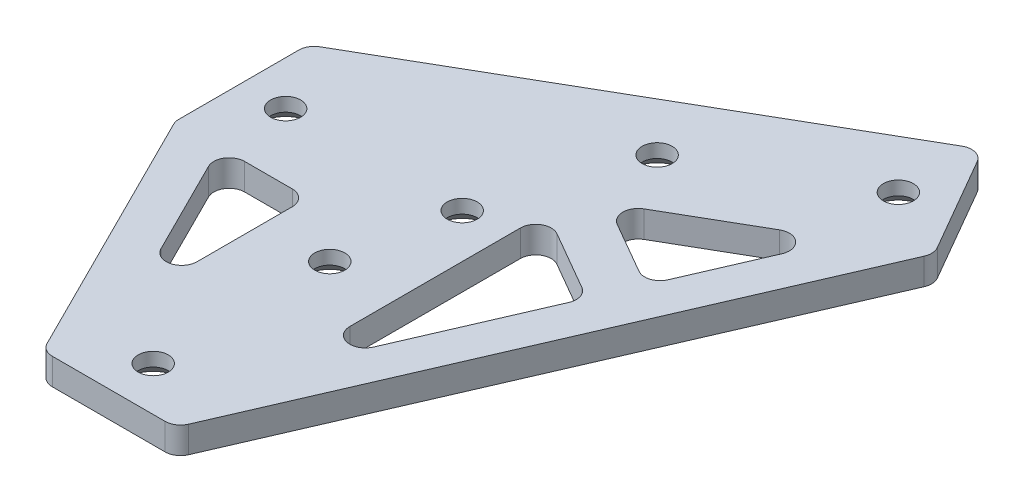
SolidWorks part; units mm, degrees
ref_plane "正面" through (0, 0, 0) normal (0, 0, 1) x (1, 0, 0)
ref_plane "平面" through (0, 0, 0) normal (0, 1, 0) x (1, 0, 0)
ref_plane "右側面" through (0, 0, 0) normal (1, 0, 0) x (0, 0, -1)
sketch "ｽｹｯﾁ2" plane through (0, 0.3953, 0) normal (0, 1, 0) x (1, 0, 0)
  line L0 (275.032, 154.7676) -> (267.532, 167.7579) construction
  line L1 (267.532, 167.7579) -> (163.6089, 107.7579) construction
  line L2 (163.6089, 107.7579) -> (171.1089, 94.7676) construction
  line L3 (171.1089, 94.7676) -> (275.032, 154.7676) construction
  line L4 (171.1089, 79.7676) -> (156.1089, 79.7676) construction
  line L5 (156.1089, 79.7676) -> (156.1089, -61.2324) construction
  line L6 (156.1089, -61.2324) -> (171.1089, -61.2324) construction
  line L7 (171.1089, -61.2324) -> (171.1089, 79.7676) construction
  line L8 (171.1089, 79.7676) -> (171.1089, 94.7676) construction
  line L9 (171.1089, 94.7676) -> (-48.8911, 94.7676) construction
  line L10 (-48.8911, 94.7676) -> (-48.8911, 79.7676) construction
  line L11 (-48.8911, 79.7676) -> (171.1089, 79.7676) construction
  line L12 (275.032, 154.7676) -> (267.532, 167.7579) construction
  line L13 (267.532, 167.7579) -> (163.6089, 107.7579) construction
  line L14 (163.6089, 107.7579) -> (171.1089, 94.7676) construction
  line L15 (171.1089, 94.7676) -> (275.032, 154.7676) construction
  line L16 (171.1089, 79.7676) -> (156.1089, 79.7676) construction
  line L17 (156.1089, 79.7676) -> (156.1089, -61.2324) construction
  line L18 (156.1089, -61.2324) -> (171.1089, -61.2324) construction
  line L19 (171.1089, -61.2324) -> (171.1089, 79.7676) construction
  line L20 (171.1089, 79.7676) -> (171.1089, 94.7676) construction
  line L21 (171.1089, 94.7676) -> (-48.8911, 94.7676) construction
  line L22 (-48.8911, 94.7676) -> (-48.8911, 79.7676) construction
  line L23 (-48.8911, 79.7676) -> (171.1089, 79.7676) construction
  line L24 (0, 15) -> (103.923, 75) construction
  line L25 (0, 0) -> (-220, 0) construction
  line L26 (0, 0) -> (0, 15) construction
  line L27 (0, 15) -> (-220, 15) construction
  line L28 (-220, 0) -> (-220, 15) construction
  line L29 (0, 0) -> (-15, 0) construction
  line L30 (0, 0) -> (0, -141) construction
  line L31 (0, -141) -> (-15, -141) construction
  line L32 (-15, 0) -> (-15, -141) construction
  line L33 (103.923, 75) -> (96.423, 87.9904) construction
  line L34 (96.423, 87.9904) -> (-7.5, 27.9904) construction
  line L35 (-7.5, 27.9904) -> (0, 15) construction
  dimension "D1" = 15
  dimension "D2" = 220
  dimension "D3" = 141
  dimension "D4" = 15
  dimension "D5" = 120
  dimension "D6" = 15
  dimension "D7" = 120
sketch "ｽｹｯﾁ4" plane through (0, 0, 0) normal (0, 1, 0) x (1, 0, 0)
  line L0 (103.923, 75) -> (96.423, 87.9904) construction
  line L1 (0, 15) -> (103.923, 75) construction
  line L2 (96.423, 87.9904) -> (-7.5, 27.9904) construction
  line L3 (-7.5, 27.9904) -> (0, 15) construction
  line L4 (0, -141) -> (-15, -141) construction
  line L5 (0, 0) -> (0, -141) construction
  line L6 (-15, 0) -> (-15, -141) construction
  line L7 (0, 0) -> (0, 15) construction
  line L8 (-220, 0) -> (-220, 15) construction
  line L9 (0, 0) -> (-220, 0) construction
  line L10 (0, 15) -> (-220, 15) construction
  line L11 (103.923, 75) -> (96.423, 87.9904) construction
  line L12 (0, 15) -> (103.923, 75) construction
  line L13 (96.423, 87.9904) -> (-7.5, 27.9904) construction
  line L14 (-7.5, 27.9904) -> (0, 15) construction
  line L15 (0, -141) -> (-15, -141) construction
  line L16 (0, 0) -> (0, -141) construction
  line L17 (-15, 0) -> (-15, -141) construction
  line L18 (0, 0) -> (0, 15) construction
  line L19 (-220, 0) -> (-220, 15) construction
  line L20 (0, 0) -> (-220, 0) construction
  line L21 (0, 15) -> (-220, 15) construction
  line L22 (-3.75, 21.4952) -> (17.9006, 33.9952) construction
  line L23 (0, 7.5) -> (-25, 7.5) construction
  line L24 (-7.5, 0) -> (-7.5, -25) construction
  line L25 (-30, 0) -> (-30, 15)
  line L26 (-30, 15) -> (18.4808, 42.9904)
  line L27 (18.4808, 42.9904) -> (25.9808, 30)
  line L28 (25.9808, 30) -> (0, -30)
  line L29 (0, -30) -> (-15, -30)
  line L30 (-15, -30) -> (-30, 0)
  circle A0 centre (0.5801, 23.9952) radius 1.6
  circle A1 centre (-5, 7.5) radius 1.6
  circle A2 centre (-7.5, -5) radius 1.6
  circle A3 centre (-7.5, -25) radius 1.6
  circle A4 centre (-25, 7.5) radius 1.6
  circle A5 centre (17.9006, 33.9952) radius 1.6
  dimension "D4" = 3.2
  dimension "D5" = 3.2
  dimension "D6" = 3.2
  dimension "D7" = 3.2
  dimension "D8" = 3.2
  dimension "D9" = 3.2
  dimension "D1" = 25
  dimension "D2" = 25
  dimension "D3" = 25
  dimension "D10" = 20
  dimension "D11" = 20
  dimension "D12" = 20
  dimension "D13" = 5
  dimension "D14" = 5
  dimension "D15" = 5
extrude "ﾎﾞｽ - 押し出し1" add sketch "ｽｹｯﾁ4" along normal mid plane 3
sketch "ｽｹｯﾁ5" plane through (0, 1.5, 0) normal (0, 1, 0) x (1, 0, 0)
  line L0 (-7.5, 27.9904) -> (0, 15) construction
  line L1 (0, 15) -> (103.923, 75) construction
  line L2 (0, 0) -> (0, 15) construction
  line L3 (0, 15) -> (-220, 15) construction
  line L4 (0, 0) -> (-220, 0) construction
  line L5 (-15, 0) -> (-15, -141) construction
  line L6 (-30, 0) -> (-15, -30)
  line L7 (-15, -30) -> (0, -30)
  line L8 (0, -30) -> (25.9808, 30)
  line L9 (25.9808, 30) -> (18.4808, 42.9904)
  line L10 (18.4808, 42.9904) -> (-30, 15)
  line L11 (-30, 15) -> (-30, 0)
  line L12 (-30, 0) -> (-15, -30)
  line L13 (-15, -30) -> (0, -30)
  line L14 (0, -30) -> (25.9808, 30)
  line L15 (25.9808, 30) -> (18.4808, 42.9904)
  line L16 (18.4808, 42.9904) -> (-30, 15)
  line L17 (-30, 15) -> (-30, 0)
  line L18 (0, 0) -> (0, -141) construction
  line L19 (-7.5, 27.9904) -> (0, 15)
  line L20 (0, 15) -> (103.923, 75)
  line L21 (0, 0) -> (0, 15)
  line L22 (0, 15) -> (-220, 15)
  line L23 (0, 0) -> (-220, 0)
  line L24 (-15, 0) -> (-15, -141)
  line L25 (0, 0) -> (0, -141)
  line L26 (-2.9552, -25.5) -> (20.9517, 29.7106)
  line L27 (20.9517, 29.7106) -> (16.8336, 36.8433)
  line L28 (16.8336, 36.8433) -> (-25.5, 12.4019)
  line L29 (-25.5, 12.4019) -> (-25.5, 1.0623)
  line L30 (-25.5, 1.0623) -> (-12.2188, -25.5)
  line L31 (-12.2188, -25.5) -> (-2.9552, -25.5)
  line L32 (0, 15) -> (11.6654, 8.265) construction
  line L33 (0, 15) -> (-10.5, 21.0622) construction
  line L34 (-13, 19.6188) -> (10.6654, 5.9555)
  line L37 (-21, 15) -> (-5.25, 24.0933) construction
  line L38 (12.6654, 10.5744) -> (-8, 22.5056)
  line L40 (0, 15) -> (3.4641, 13)
  line L41 (0, 15) -> (-3.4641, 17)
  line L42 (-4.6188, 15) -> (-2.3094, 19)
  line L43 (0, 7) -> (6.9282, 19)
  line L44 (1.25, 17.1651) -> (-9.25, 23.2272) construction
  line L47 (-1.25, 12.8349) -> (10.4154, 6.0999) construction
  circle A1 centre (0.5801, 23.9952) radius 1.6
  circle A2 centre (0.5801, 23.9952) radius 1.6
  circle A3 centre (-5, 7.5) radius 1.6
  circle A4 centre (-5, 7.5) radius 1.6
  circle A5 centre (-7.5, -5) radius 1.6
  circle A6 centre (-7.5, -5) radius 1.6
  circle A7 centre (-7.5, -25) radius 1.6
  circle A8 centre (-7.5, -25) radius 1.6
  circle A9 centre (-25, 7.5) radius 1.6
  circle A10 centre (-25, 7.5) radius 1.6
  circle A11 centre (17.9006, 33.9952) radius 1.6
  circle A12 centre (17.9006, 33.9952) radius 1.6
  point P58 (-3.4641, 17)
  point P61 (3.4641, 13)
  dimension "D9" = 2.5
  dimension "D12" = 60
  dimension "D13" = 4
  dimension "D14" = 4
  dimension "D1" = 0
  dimension "D2" = 0
  dimension "D3" = 0
  dimension "D4" = 0
  dimension "D5" = 0
  dimension "D6" = 0
  dimension "D7" = 0
  dimension "D8" = 4.5
extrude "ｶｯﾄ - 押し出し2" cut sketch "ｽｹｯﾁ5" against normal blind 3 contours L43 L38 L26 L20 | L38 L43 L20 | L21 L43 L34 | L43 L21 L25 L26 L34 | L23 L30 L24
fillet "ﾌｨﾚｯﾄ2" radius 1.75 15 edges at (-15, 0, 19.9377) (0, 0, 18.6752) (10.6654, 0, -5.9555) (12.6654, 0, -10.5744) (2.5, 0, -16.4434) (19.4424, 0, -26.2251) (-24.9688, 0, 0) (-15, 0, 30) (0, 0, 30) (25.9808, 0, -30) (18.4808, 0, -42.9904) (-30, 0, -15) (-30, 0, 0) (0, 0, -12.1132) (-15, 0, 0)
sketch "ｽｹｯﾁ6" plane through (0, -1.5, 0) normal (0, -1, 0) x (1, 0, 0)
  line L3 (2.625, -10.5977) -> (9.3148, -6.7353)
  line L4 (0, 10.2297) -> (0, -9.0822)
  line L5 (10.0457, -4.5244) -> (3.3559, 10.9251)
  line L6 (2.625, -10.5977) -> (9.3148, -6.7353)
  line L7 (0, 10.2297) -> (0, -9.0822)
  line L8 (10.0457, -4.5244) -> (3.3559, 10.9251)
  line L9 (-15, 1.75) -> (-15, 12.5246)
  line L10 (-22.1373, 0) -> (-16.75, 0)
  line L11 (-18.3152, 13.3072) -> (-23.7025, 2.5326)
  line L12 (-15, 1.75) -> (-15, 12.5246)
  line L13 (-22.1373, 0) -> (-16.75, 0)
  line L14 (-18.3152, 13.3072) -> (-23.7025, 2.5326)
  line L15 (10.9648, -11.5562) -> (5.125, -14.9278)
  line L16 (17.339, -21.3674) -> (13.4457, -12.3764)
  line L17 (5.125, -17.9589) -> (14.8581, -23.5783)
  line L18 (10.9648, -11.5562) -> (5.125, -14.9278)
  line L19 (17.339, -21.3674) -> (13.4457, -12.3764)
  line L20 (5.125, -17.9589) -> (14.8581, -23.5783)
  circle A1 centre (-25, -7.5) radius 1.6
  circle A2 centre (-25, -7.5) radius 1.6
  arc A3 (0, -9.0822) -> (2.625, -10.5977) centre (1.75, -9.0822) ccw
  arc A4 (3.3559, 10.9251) -> (0, 10.2297) centre (1.75, 10.2297) ccw
  arc A5 (9.3148, -6.7353) -> (10.0457, -4.5244) centre (8.4398, -5.2198) ccw
  arc A6 (0, -9.0822) -> (2.625, -10.5977) centre (1.75, -9.0822) ccw
  arc A7 (3.3559, 10.9251) -> (0, 10.2297) centre (1.75, 10.2297) ccw
  arc A8 (9.3148, -6.7353) -> (10.0457, -4.5244) centre (8.4398, -5.2198) ccw
  arc A9 (-16.75, 0) -> (-15, 1.75) centre (-16.75, 1.75) ccw
  arc A10 (-23.7025, 2.5326) -> (-22.1373, 0) centre (-22.1373, 1.75) ccw
  arc A11 (-15, 12.5246) -> (-18.3152, 13.3072) centre (-16.75, 12.5246) ccw
  arc A12 (-16.75, 0) -> (-15, 1.75) centre (-16.75, 1.75) ccw
  arc A13 (-23.7025, 2.5326) -> (-22.1373, 0) centre (-22.1373, 1.75) ccw
  arc A14 (-15, 12.5246) -> (-18.3152, 13.3072) centre (-16.75, 12.5246) ccw
  circle A15 centre (-7.5, 5) radius 1.6
  circle A16 centre (-7.5, 5) radius 1.6
  circle A17 centre (0.5801, -23.9952) radius 1.6
  circle A18 centre (0.5801, -23.9952) radius 1.6
  circle A19 centre (-5, -7.5) radius 1.6
  circle A20 centre (-5, -7.5) radius 1.6
  circle A21 centre (-7.5, 25) radius 1.6
  circle A22 centre (-7.5, 25) radius 1.6
  circle A23 centre (17.9006, -33.9952) radius 1.6
  circle A24 centre (17.9006, -33.9952) radius 1.6
  arc A27 (13.4457, -12.3764) -> (10.9648, -11.5562) centre (11.8398, -13.0717) ccw
  arc A28 (14.8581, -23.5783) -> (17.339, -21.3674) centre (15.7331, -22.0628) ccw
  arc A29 (5.125, -14.9278) -> (5.125, -17.9589) centre (6, -16.4434) ccw
  arc A30 (13.4457, -12.3764) -> (10.9648, -11.5562) centre (11.8398, -13.0717) ccw
  arc A31 (14.8581, -23.5783) -> (17.339, -21.3674) centre (15.7331, -22.0628) ccw
  arc A32 (5.125, -14.9278) -> (5.125, -17.9589) centre (6, -16.4434) ccw
  dimension "D1" = 0
  dimension "D2" = 0
  dimension "D3" = 0
  dimension "D4" = 0
  dimension "D5" = 0
  dimension "D6" = 0
  dimension "D7" = 0
  dimension "D8" = 0
  dimension "D9" = 0
hole_wizard "M3 丸皿ねじ用皿穴1" positions "3Dｽｹｯﾁ1" profile "ｽｹｯﾁ7" countersink size "M3" standard "ISO"
sketch3d "3Dｽｹｯﾁ1"
  point P0 (-7.5, -1.5, 25)
  point P3 (-7.5, -1.5, 5)
  point P6 (-25, -1.5, -7.5)
  point P9 (-5, -1.5, -7.5)
  point P12 (0.5801, -1.5, -23.9952)
  point P15 (17.9006, -1.5, -33.9952)
sketch "ｽｹｯﾁ7" plane through (-7.5, -1.5, 25) normal (1, 0, 0) x (0, 0, -1)
  line L0 (0, 0) -> (0, 7)
  line L1 (0, 7) -> (1.7, 5.9785)
  line L2 (1.7, 5.9785) -> (1.7, 1.45)
  line L3 (1.7, 1.45) -> (3.15, 0)
  line L5 (3.15, 0) -> (0, 0)
  line L6 (-1.7, 1.45) -> (-3.15, 0) construction
  line L10 (0, 7) -> (-1.7, 5.9785) construction
  line L11 (0, -6.35) -> (0, 107.95) construction
  dimension "穴の直径" = 3.4
  dimension "穴の深さ" = 7
  dimension "表面の皿穴の直径" = 6.3
  dimension "表面の皿穴の角度" = 90
  dimension "ﾄﾞﾘﾙ角度" = 118
